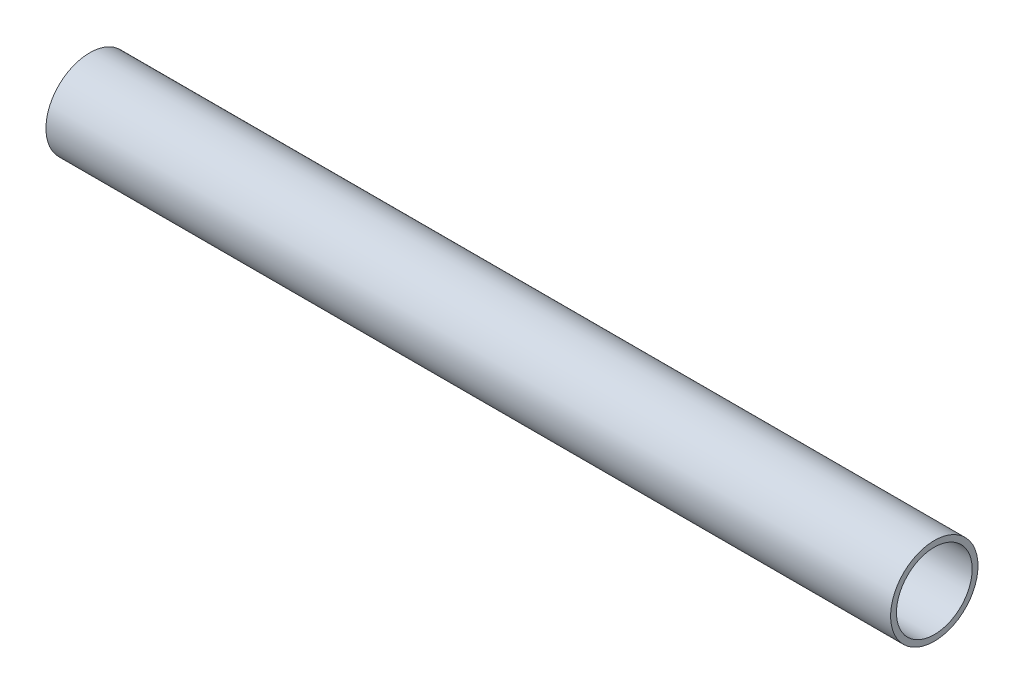
SolidWorks part; units mm, degrees
ref_plane "Front Plane" through (0, 0, 0) normal (0, 0, 1) x (1, 0, 0)
ref_plane "Top Plane" through (0, 0, 0) normal (0, 1, 0) x (1, 0, 0)
ref_plane "Right Plane" through (0, 0, 0) normal (1, 0, 0) x (0, 0, -1)
sketch "Sketch1" plane through (0, 0, 0) normal (1, 0, 0) x (0, 0, -1)
  circle A0 centre (0, 0) radius 7.5
  circle A1 centre (0, 0) radius 6.5
  dimension "D1" = 15
  dimension "D2" = 13
extrude "Boss-Extrude1" add sketch "Sketch1" along normal blind 145
